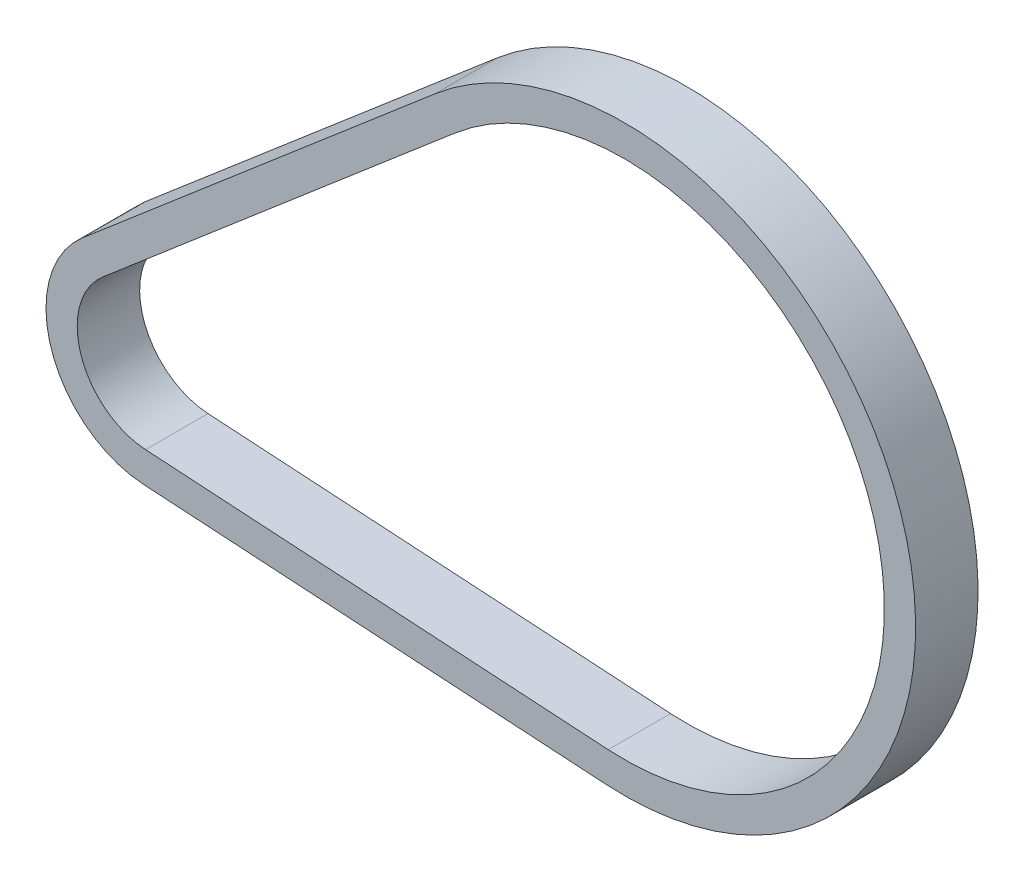
SolidWorks part; units mm, degrees
ref_plane "Front Plane" through (0, 0, 0) normal (0, 0, 1) x (1, 0, 0)
ref_plane "Top Plane" through (0, 0, 0) normal (0, 1, 0) x (1, 0, 0)
ref_plane "Right Plane" through (0, 0, 0) normal (1, 0, 0) x (0, 0, -1)
sketch "Sketch1" plane through (0, 0, 0) normal (0, 0, 1) x (1, 0, 0)
  line L0 (0, 0) -> (1, 0) construction
  line L1 (0, 0) -> (0, 1) construction
  line L2 (-1.6276, -26.4082) -> (-48.6668, -23.5091)
  line L3 (-53.0215, -10.4807) -> (-17.1804, 20.1216)
  arc A0 (-17.1804, 20.1216) -> (-1.6276, -26.4082) centre (0, 0) cw
  arc A1 (-48.6668, -23.5091) -> (-53.0215, -10.4807) centre (-48.211, -16.1147) cw
  point P10 (0, 0)
  dimension "D1" = 26.4583
  dimension "D3" = 7.4083
  dimension "D2" = 47.1284
  dimension "D4" = 1.6276
extrude "Extrude-Thin1" add sketch "Sketch1" along normal blind 3.175 and the other way blind 3.175 thin thin type one direction wall 3.175
